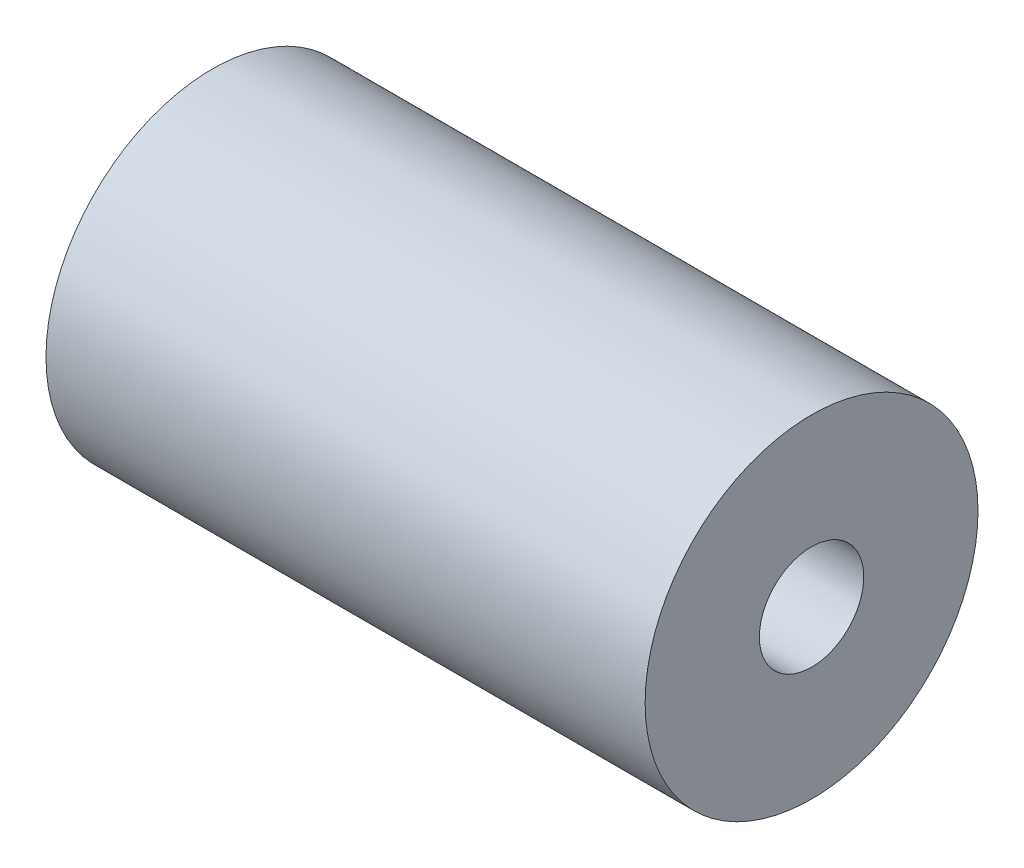
SolidWorks part; units mm, degrees
material "6061-T6 (SS)"
ref_plane "Front Plane" through (0, 0, 0) normal (0, 0, 1) x (1, 0, 0)
ref_plane "Top Plane" through (0, 0, 0) normal (0, 1, 0) x (1, 0, 0)
ref_plane "Right Plane" through (0, 0, 0) normal (1, 0, 0) x (0, 0, -1)
sketch "Sketch1" plane through (0, 0, 0) normal (0, 1, 0) x (1, 0, 0)
  line L0 (-72.894, 0) -> (78.2697, 0) construction
  line L1 (-14.2875, 7.9375) -> (-14.2875, 2.4892)
  line L2 (-14.2875, 7.9375) -> (14.2875, 7.9375)
  line L3 (-14.2875, 2.4892) -> (14.2875, 2.4892)
  line L4 (14.2875, 7.9375) -> (14.2875, 2.4892)
  line L5 (0, 0) -> (0, 2.4892) construction
  dimension "D1" = 15.875
  dimension "D2" = 4.9784
  dimension "D3" = 28.575
revolve "Revolve1" add sketch "Sketch1" angle 360 about L0
